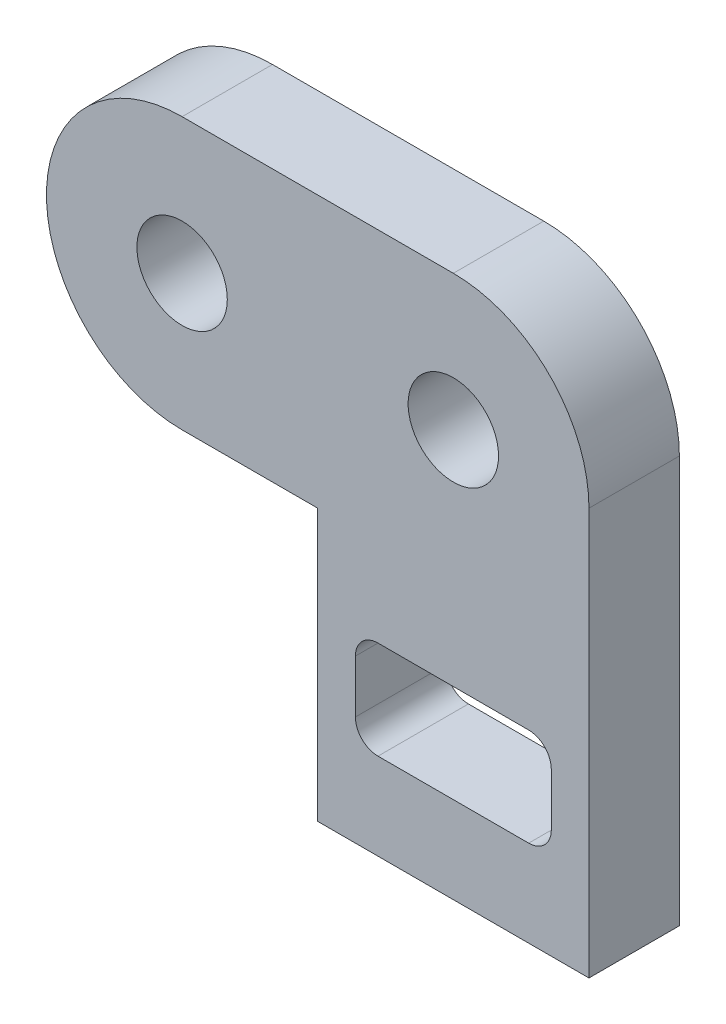
SolidWorks part; units mm, degrees
ref_plane "Alzado" through (0, 0, 0) normal (0, 0, 1) x (1, 0, 0)
ref_plane "Planta" through (0, 0, 0) normal (0, 1, 0) x (1, 0, 0)
ref_plane "Vista lateral" through (0, 0, 0) normal (1, 0, 0) x (0, 0, -1)
sketch "Model" plane through (0, 0, 0) normal (0, 0, 1) x (1, 0, 0)
  line L0 (149.3421, 211.824) -> (158.3421, 211.824)
  line L1 (153.8421, 202.824) -> (149.3421, 202.824)
  line L2 (160.8421, 196.699) -> (155.8421, 196.699)
  line L3 (155.0921, 197.449) -> (155.0921, 199.199)
  line L4 (155.8421, 199.949) -> (160.8421, 199.949)
  line L5 (161.5921, 199.199) -> (161.5921, 197.449)
  line L6 (153.8421, 193.824) -> (162.8421, 193.824)
  line L7 (153.8421, 202.824) -> (153.8421, 193.824)
  line L8 (162.8421, 207.324) -> (162.8421, 193.824)
  arc A0 (149.3421, 211.824) -> (149.3421, 202.824) centre (149.3421, 207.324) ccw
  arc A1 (162.8421, 207.324) -> (158.3421, 211.824) centre (158.3421, 207.324) ccw
  circle A2 centre (149.3421, 207.324) radius 1.5
  circle A3 centre (158.3421, 207.324) radius 1.5
  arc A4 (155.0921, 197.449) -> (155.8421, 196.699) centre (155.8421, 197.449) ccw
  arc A5 (155.8421, 199.949) -> (155.0921, 199.199) centre (155.8421, 199.199) ccw
  arc A6 (161.5921, 199.199) -> (160.8421, 199.949) centre (160.8421, 199.199) ccw
  arc A7 (160.8421, 196.699) -> (161.5921, 197.449) centre (160.8421, 197.449) ccw
extrude "Saliente-Extruir1" add sketch "Model" along normal blind 3
